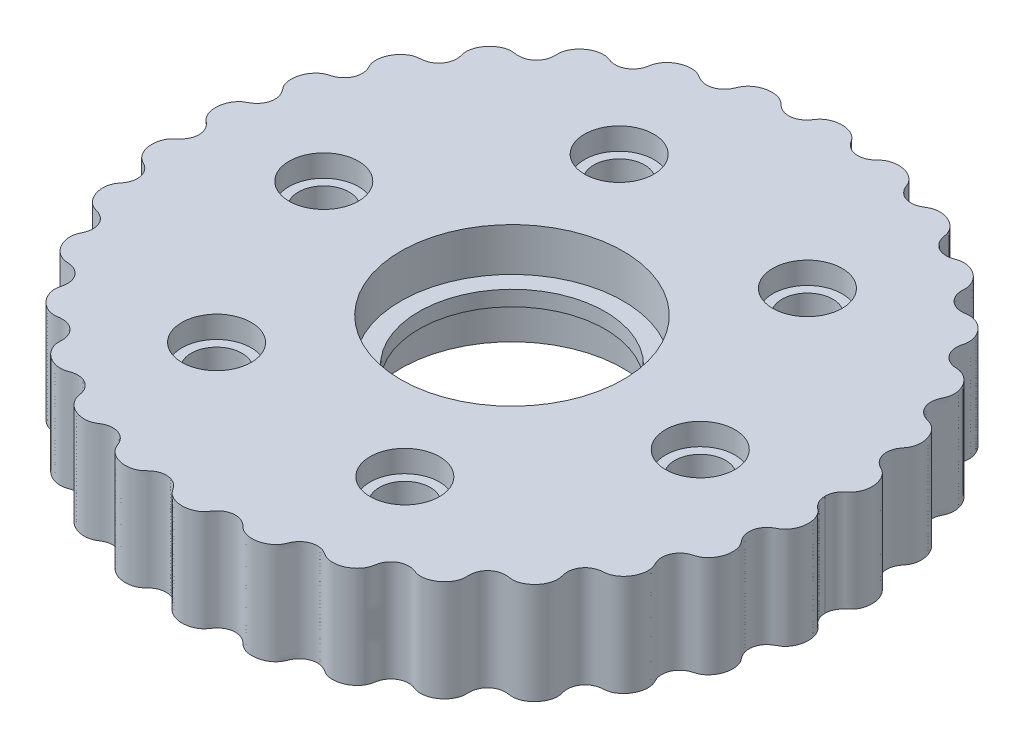
SolidWorks part; units mm, degrees
ref_plane "Front Plane" through (0, 0, 0) normal (0, 0, 1) x (1, 0, 0)
ref_plane "Top Plane" through (0, 0, 0) normal (0, 1, 0) x (1, 0, 0)
ref_plane "Right Plane" through (0, 0, 0) normal (1, 0, 0) x (0, 0, -1)
sketch "Sketch5" plane through (0, 0, 0) normal (0, 1, 0) x (1, 0, 0)
  line L0 (-37, 0) -> (37, 0) construction
  spline S0 degree 4 poles (33.6201, 15.9032) (33.6202, 15.6059) (33.7016, 15.1701) (33.9687, 14.6432) (34.4643, 14.1903) (34.8255, 13.9864) (35.1244, 13.8732) (35.3415, 13.8086) (35.5156, 13.7581) (35.7286, 13.6806) (35.9914, 13.5445) (36.2852, 13.3283) (36.665, 12.9337) (36.969, 12.4366) (37.1692, 11.88) (37.2514, 11.2873) (37.2381, 10.8555) (37.1706, 10.4918) (37.0784, 10.2135) (36.9889, 10.0153) (36.8865, 9.8401) (36.7761, 9.6875) (36.6303, 9.5028) (36.4666, 9.2723) (36.3182, 8.9951) (36.2055, 8.6691) (36.1476, 8.346) (36.1382, 8.0344) (36.1741, 7.7336) (36.2499, 7.4499) (36.3608, 7.1872) (36.4999, 6.9493) (36.6697, 6.7308) (36.8638, 6.5368) (37.0837, 6.3658) (37.2851, 6.2419) (37.4707, 6.1434) (37.6377, 6.0496) (37.7133, 6.0018) (37.8076, 5.9345) (37.8984, 5.863) (37.9811, 5.7906) (38.0693, 5.7029) (38.1661, 5.5944) (38.2783, 5.4519) (38.399, 5.2711) (38.5204, 5.048) (38.632, 4.7801) (38.7165, 4.5026) (38.7833, 4.1716) (38.8153, 3.7874) (38.7918, 3.3544) (38.7009, 2.943) (38.5724, 2.606) (38.4358, 2.3521) (38.3147, 2.1727) (38.1838, 2.0152) (38.0457, 1.8805) (37.8982, 1.7564) (37.7521, 1.6308) (37.5791, 1.4629) (37.4056, 1.2571) (37.2454, 1.0066) (37.0836, 0.6399) (36.9813, 0.1918) (36.9899, -0.2712) (37.1093, -0.7163) (37.2863, -1.079) (37.4568, -1.3245) (37.6384, -1.5249) (37.8168, -1.688) (37.9652, -1.8118) (38.1102, -1.9399) (38.2421, -2.0817) (38.365, -2.2432) (38.4766, -2.4235) (38.6007, -2.6735) (38.7542, -3.1094) (38.8303, -3.6329) (38.7943, -4.224) (38.6368, -4.7979) (38.4589, -5.1833) (38.2594, -5.4872) (38.0695, -5.707) (37.9109, -5.8569) (37.747, -5.9826) (37.5812, -6.0843) (37.4093, -6.175) (37.2395, -6.2696) (37.0351, -6.4013) (36.8234, -6.5711) (36.6166, -6.7879) (36.3864, -7.1195) (36.2027, -7.5374) (36.124, -7.9871) (36.1536, -8.4372) (36.2505, -8.8154) (36.363, -9.0822) (36.4942, -9.3093) (36.6301, -9.501) (36.7457, -9.6491) (36.8873, -9.8367) (37.0113, -10.0513) (37.1094, -10.2922) (37.1963, -10.6114) (37.2619, -11.0816) (37.2287, -11.6216) (37.0672, -12.2031) (36.7876, -12.7384) (36.5295, -13.0795) (36.2674, -13.3353) (36.0326, -13.51) (35.8436, -13.6225) (35.6546, -13.7096) (35.4689, -13.7728) (35.2331, -13.8388) (34.9539, -13.9315) (34.663, -14.073) (34.3764, -14.2756) (34.0851, -14.5596) (33.8252, -14.936) (33.6633, -15.3628) (33.6075, -15.809) (33.6302, -16.1955) (33.6888, -16.4767) (33.7726, -16.723) (33.867, -16.9362) (33.9492, -17.1036) (34.0456, -17.316) (34.1183, -17.551) (34.1611, -17.8055) (34.1766, -18.1335) (34.14, -18.603) (33.9938, -19.1195) (33.7153, -19.6496) (33.3326, -20.1109) (33.0116, -20.3886) (32.7046, -20.5829) (32.4408, -20.7045) (32.2343, -20.7752) (32.033, -20.8216) (31.8399, -20.8454) (31.6459, -20.8581) (31.4523, -20.8764) (31.2122, -20.9152) (30.9459, -20.9874) (30.6617, -21.1078) (30.3048, -21.3326) (29.9643, -21.6601) (29.7179, -22.0563) (29.577, -22.489) (29.5259, -22.8695) (29.5291, -23.1544) (29.563, -23.4104) (29.6127, -23.6364) (29.6581, -23.8158) (29.7052, -24.0426) (29.7238, -24.2861) (29.7102, -24.5417) (29.6547, -24.8628) (29.519, -25.3099) (29.267, -25.7821) (28.8818, -26.2416) (28.4067, -26.613) (28.0278, -26.8178) (27.6806, -26.9421) (27.3918, -27.003) (27.1705, -27.0259) (26.9596, -27.0248) (26.7616, -27.0031) (26.5647, -26.9745) (26.3665, -26.955) (26.1175, -26.9486) (25.761, -26.9788) (25.3089, -27.1043) (24.824, -27.3909) (24.4148, -27.8339) (24.1717, -28.3154) (24.0729, -28.7303) (24.0489, -29.0616) (24.0521, -29.3012) (24.0594, -29.4928) (24.0546, -29.7327) (24.0067, -30.0355) (23.8897, -30.3895) (23.6285, -30.877) (23.2487, -31.3196) (22.7798, -31.682) (22.2395, -31.9429) (21.8227, -32.063) (21.4542, -32.11) (21.1569, -32.1068) (20.9344, -32.0806) (20.7275, -32.0326) (20.5377, -31.9678) (20.3495, -31.899) (20.1577, -31.84) (19.9131, -31.7845) (19.5549, -31.7447) (19.0835, -31.7814) (18.5507, -31.9717) (18.1214, -32.2883) (17.8376, -32.6242) (17.6504, -32.9447) (17.5448, -33.2022) (17.4764, -33.4473) (17.4324, -33.6738) (17.4006, -33.8556) (17.3478, -34.0803) (17.2617, -34.3078) (17.1426, -34.5327) (16.9591, -34.7991) (16.6522, -35.1459) (16.2287, -35.47) (15.6877, -35.7293) (15.0983, -35.8712) (14.6623, -35.8998) (14.2898, -35.8662) (13.9982, -35.7981) (13.7853, -35.7234) (13.5928, -35.6303) (13.4203, -35.5252) (13.2488, -35.4186) (13.0713, -35.3221) (12.8406, -35.2189) (12.4944, -35.1096) (12.0211, -35.0548) (11.4595, -35.141) (10.9769, -35.3716) (10.6351, -35.6476) (10.3919, -35.9248) (10.2401, -36.1555) (10.1263, -36.3806) (10.0387, -36.5915) (9.9697, -36.7607) (9.8693, -36.966) (9.7364, -37.1668) (9.5727, -37.3587) (9.3378, -37.5772) (8.9665, -37.8479) (8.4908, -38.0712) (7.9192, -38.2085) (7.3291, -38.2262) (6.9124, -38.1699) (6.5666, -38.0695) (6.2983, -37.9513) (6.1011, -37.8386) (5.9227, -37.7081) (5.7648, -37.5629) (5.6114, -37.4135) (5.4491, -37.2733) (5.2327, -37.1149) (4.9037, -36.9312) (4.4389, -36.7814) (3.8653, -36.7592) (3.2834, -36.9106) (2.8288, -37.176) (2.5313, -37.4532) (2.3359, -37.6983) (2.2101, -37.8812) (2.1102, -38.0281) (1.9736, -38.2034) (1.7711, -38.4048) (1.4894, -38.6107) (1.026, -38.8446) (0.498, -38.9852) (-0.0532, -39.0229) (-0.6059, -38.9535) (-0.99, -38.8438) (-1.303, -38.7063) (-1.5774, -38.5452) (-1.7771, -38.395) (-1.9495, -38.23) (-2.0917, -38.0539) (-2.1944, -37.9049) (-2.3215, -37.7179) (-2.518, -37.4668) (-2.8184, -37.1828) (-3.2772, -36.9124) (-3.8631, -36.7591) (-4.4389, -36.7814) (-4.9037, -36.9312) (-5.2327, -37.1149) (-5.4491, -37.2733) (-5.6114, -37.4135) (-5.7648, -37.5629) (-5.9227, -37.7081) (-6.1011, -37.8386) (-6.2983, -37.9513) (-6.5666, -38.0695) (-6.9124, -38.1699) (-7.3291, -38.2262) (-7.9192, -38.2085) (-8.4908, -38.0712) (-8.9665, -37.8479) (-9.3378, -37.5772) (-9.5727, -37.3587) (-9.7364, -37.1668) (-9.8693, -36.966) (-9.9697, -36.7607) (-10.0387, -36.5915) (-10.1263, -36.3806) (-10.2713, -36.0937) (-10.5133, -35.755) (-10.9138, -35.4018) (-11.4595, -35.141) (-12.0211, -35.0548) (-12.4944, -35.1096) (-12.8406, -35.2189) (-13.0713, -35.3221) (-13.2488, -35.4186) (-13.4203, -35.5252) (-13.5928, -35.6303) (-13.7853, -35.7234) (-13.9982, -35.7981) (-14.2898, -35.8662) (-14.6623, -35.8998) (-15.0983, -35.8712) (-15.6877, -35.7293) (-16.2287, -35.47) (-16.6522, -35.1459) (-16.9591, -34.7991) (-17.1426, -34.5327) (-17.2617, -34.3078) (-17.3478, -34.0803) (-17.4006, -33.8556) (-17.4324, -33.6738) (-17.4764, -33.4473) (-17.5448, -33.2022) (-17.6504, -32.9447) (-17.8376, -32.6242) (-18.1214, -32.2883) (-18.5507, -31.9717) (-19.0835, -31.7814) (-19.5549, -31.7447) (-19.9131, -31.7845) (-20.1577, -31.84) (-20.3495, -31.899) (-20.5377, -31.9678) (-20.7275, -32.0326) (-20.9344, -32.0806) (-21.1569, -32.1068) (-21.4542, -32.11) (-21.8227, -32.063) (-22.2395, -31.9429) (-22.7798, -31.682) (-23.2487, -31.3196) (-23.6285, -30.877) (-23.8897, -30.3895) (-24.0067, -30.0355) (-24.0546, -29.7327) (-24.0594, -29.4928) (-24.0521, -29.3012) (-24.0489, -29.0616) (-24.0729, -28.7303) (-24.1717, -28.3154) (-24.4148, -27.8339) (-24.824, -27.3909) (-25.3089, -27.1043) (-25.761, -26.9788) (-26.1175, -26.9486) (-26.3665, -26.955) (-26.5647, -26.9745) (-26.7616, -27.0031) (-26.9596, -27.0248) (-27.1705, -27.0259) (-27.3918, -27.003) (-27.6806, -26.9421) (-28.0278, -26.8178) (-28.4067, -26.613) (-28.8818, -26.2416) (-29.267, -25.7821) (-29.519, -25.3099) (-29.6547, -24.8628) (-29.7102, -24.5417) (-29.7238, -24.2861) (-29.7052, -24.0426) (-29.6581, -23.8158) (-29.6127, -23.6364) (-29.563, -23.4104) (-29.5291, -23.1544) (-29.5259, -22.8695) (-29.577, -22.489) (-29.7179, -22.0563) (-29.9643, -21.6601) (-30.3048, -21.3326) (-30.6617, -21.1078) (-30.9459, -20.9874) (-31.2122, -20.9152) (-31.4523, -20.8764) (-31.6459, -20.8581) (-31.8399, -20.8454) (-32.033, -20.8216) (-32.2343, -20.7752) (-32.4408, -20.7045) (-32.7046, -20.5829) (-33.0116, -20.3886) (-33.3326, -20.1109) (-33.7153, -19.6496) (-33.9938, -19.1195) (-34.14, -18.603) (-34.1766, -18.1335) (-34.1611, -17.8055) (-34.1183, -17.551) (-34.0456, -17.316) (-33.9492, -17.1036) (-33.867, -16.9362) (-33.7726, -16.723) (-33.6888, -16.4767) (-33.6302, -16.1955) (-33.6075, -15.809) (-33.6633, -15.3628) (-33.8252, -14.936) (-34.0851, -14.5596) (-34.3764, -14.2756) (-34.663, -14.073) (-34.9539, -13.9315) (-35.2331, -13.8388) (-35.4689, -13.7728) (-35.6546, -13.7096) (-35.8436, -13.6225) (-36.0326, -13.51) (-36.2674, -13.3353) (-36.5295, -13.0795) (-36.7876, -12.7384) (-37.0672, -12.2031) (-37.2287, -11.6216) (-37.2619, -11.0816) (-37.1963, -10.6114) (-37.1094, -10.2922) (-37.0113, -10.0513) (-36.8873, -9.8367) (-36.7457, -9.6491) (-36.6301, -9.501) (-36.4942, -9.3093) (-36.363, -9.0822) (-36.2505, -8.8154) (-36.1536, -8.4372) (-36.124, -7.9871) (-36.2027, -7.5374) (-36.3864, -7.1195) (-36.6166, -6.7879) (-36.8234, -6.5711) (-37.0351, -6.4013) (-37.2395, -6.2696) (-37.4093, -6.175) (-37.5812, -6.0843) (-37.747, -5.9826) (-37.9109, -5.8569) (-38.0695, -5.707) (-38.2594, -5.4872) (-38.4589, -5.1833) (-38.6368, -4.7979) (-38.7943, -4.224) (-38.8303, -3.6329) (-38.7542, -3.1094) (-38.6007, -2.6735) (-38.4766, -2.4235) (-38.365, -2.2432) (-38.2421, -2.0817) (-38.1102, -1.9399) (-37.9652, -1.8118) (-37.8168, -1.688) (-37.6384, -1.5249) (-37.4568, -1.3245) (-37.2863, -1.079) (-37.1093, -0.7163) (-36.9899, -0.2712) (-36.9813, 0.1918) (-37.0836, 0.6399) (-37.2454, 1.0066) (-37.4056, 1.2571) (-37.5791, 1.4629) (-37.7521, 1.6308) (-37.8982, 1.7564) (-38.0457, 1.8805) (-38.1838, 2.0152) (-38.3147, 2.1727) (-38.4358, 2.3521) (-38.5724, 2.606) (-38.7009, 2.943) (-38.7918, 3.3544) (-38.8153, 3.7874) (-38.7833, 4.1716) (-38.7166, 4.5025) (-38.6319, 4.7801) (-38.5205, 5.0479) (-38.3815, 5.3031) (-38.2372, 5.5113) (-38.0948, 5.6776) (-37.9681, 5.8034) (-37.8575, 5.8983) (-37.7246, 5.9947) (-37.6376, 6.0497) (-37.4708, 6.1433) (-37.2851, 6.2419) (-37.0838, 6.3658) (-36.8638, 6.5368) (-36.6697, 6.7308) (-36.4999, 6.9493) (-36.3608, 7.1872) (-36.2499, 7.4499) (-36.1741, 7.7336) (-36.1382, 8.0344) (-36.1476, 8.346) (-36.2055, 8.6691) (-36.3182, 8.9951) (-36.4666, 9.2723) (-36.6303, 9.5028) (-36.7761, 9.6875) (-36.8865, 9.8401) (-36.9889, 10.0153) (-37.0784, 10.2135) (-37.1706, 10.4918) (-37.2381, 10.8555) (-37.2514, 11.2873) (-37.1815, 11.7914) (-37.0233, 12.2913) (-36.8053, 12.7086) (-36.5571, 13.0424) (-36.315, 13.2895) (-36.1009, 13.4649) (-35.8769, 13.6072) (-35.6471, 13.7153) (-35.4163, 13.7882) (-35.1948, 13.8503) (-34.9234, 13.9467) (-34.613, 14.1006) (-34.2264, 14.3849) (-33.8416, 14.866) (-33.6649, 15.3373) (-33.6202, 15.7145) (-33.6201, 15.9032) knots 0 0 0 0 0 0.006684 0.009785 0.012886 0.014922 0.015941 0.016959 0.017977 0.018995 0.021032 0.023585 0.026137 0.031243 0.034004 0.036765 0.039525 0.040906 0.042286 0.043344 0.044402 0.04546 0.046518 0.048633 0.050749 0.052495 0.05424 0.055985 0.057731 0.059277 0.060824 0.06237 0.063917 0.065463 0.06701 0.068556 0.06933 0.070103 0.070917 0.071324 0.071731 0.072545 0.073358 0.074172 0.074986 0.076614 0.078242 0.07987 0.081498 0.083125 0.085819 0.088512 0.091205 0.092551 0.093898 0.09498 0.096063 0.097146 0.098229 0.099311 0.100394 0.10256 0.104263 0.105967 0.109374 0.112808 0.114525 0.116242 0.118414 0.119501 0.120587 0.121673 0.12276 0.123846 0.124933 0.126227 0.127521 0.13011 0.135287 0.138001 0.140714 0.143428 0.144784 0.146141 0.147233 0.148325 0.149417 0.150509 0.151601 0.152694 0.154878 0.156593 0.158307 0.161737 0.165054 0.166713 0.168372 0.170483 0.171539 0.172595 0.173651 0.174706 0.176818 0.178147 0.179476 0.182134 0.187449 0.190183 0.192916 0.195649 0.197016 0.198383 0.199484 0.200585 0.201686 0.202787 0.204988 0.20719 0.208918 0.210645 0.214099 0.217389 0.219034 0.220679 0.222775 0.223822 0.22487 0.225918 0.226966 0.229061 0.23038 0.231699 0.234336 0.239611 0.242324 0.245036 0.247749 0.249105 0.250461 0.251554 0.252646 0.253739 0.254831 0.255924 0.257016 0.259201 0.261016 0.262831 0.266461 0.269723 0.271354 0.272985 0.275065 0.276105 0.277145 0.278185 0.279225 0.281305 0.282614 0.283922 0.286539 0.291773 0.294526 0.297278 0.300031 0.301407 0.302783 0.303901 0.30502 0.306138 0.307257 0.308375 0.309494 0.311731 0.315276 0.318821 0.321963 0.325104 0.327259 0.328336 0.329413 0.33049 0.331568 0.333722 0.336275 0.338828 0.343935 0.346707 0.349479 0.352252 0.353638 0.355024 0.35615 0.357277 0.358403 0.359529 0.360656 0.361782 0.364035 0.367607 0.371179 0.374303 0.375864 0.377426 0.3795 0.380536 0.381573 0.38261 0.383647 0.385721 0.387018 0.388315 0.390909 0.396097 0.398888 0.40168 0.404471 0.405867 0.407262 0.408397 0.409531 0.410666 0.4118 0.412935 0.41407 0.416339 0.419937 0.423536 0.426643 0.428196 0.42975 0.431803 0.432829 0.433856 0.434882 0.435909 0.437962 0.439249 0.440536 0.44311 0.448259 0.450946 0.453634 0.456322 0.457666 0.45901 0.460214 0.461418 0.462622 0.463826 0.46503 0.466234 0.468642 0.472266 0.47589 0.478933 0.481976 0.483972 0.48497 0.485968 0.486966 0.487964 0.48996 0.492365 0.49477 0.49958 0.502134 0.504689 0.507243 0.50852 0.509798 0.511831 0.512847 0.513864 0.51488 0.515897 0.51793 0.52102 0.52411 0.527734 0.531358 0.533766 0.53497 0.536174 0.537378 0.538582 0.539786 0.54099 0.542334 0.543678 0.546366 0.549054 0.551742 0.55689 0.559464 0.560751 0.562038 0.564091 0.565118 0.566144 0.567171 0.568197 0.57025 0.573357 0.576464 0.580063 0.583662 0.585931 0.587065 0.5882 0.589334 0.590469 0.591603 0.592738 0.594134 0.595529 0.598321 0.601112 0.603903 0.609091 0.611685 0.612982 0.614279 0.616353 0.61739 0.618427 0.619464 0.620501 0.622575 0.624136 0.625698 0.628821 0.632393 0.635966 0.638218 0.639345 0.640471 0.641597 0.642724 0.64385 0.644976 0.646363 0.647749 0.650521 0.653293 0.656065 0.661172 0.663725 0.666278 0.668433 0.66951 0.670587 0.671664 0.672742 0.674896 0.678038 0.681179 0.684725 0.68827 0.690507 0.691625 0.692743 0.693862 0.69498 0.696099 0.697217 0.698593 0.69997 0.702722 0.705475 0.708227 0.713461 0.716078 0.717386 0.718695 0.720775 0.721815 0.722855 0.723895 0.724935 0.727015 0.728646 0.730278 0.73354 0.737169 0.738984 0.740799 0.742984 0.744076 0.745169 0.746261 0.747354 0.748446 0.749539 0.750895 0.752251 0.754964 0.757677 0.760389 0.765664 0.768302 0.76962 0.770939 0.773035 0.774082 0.77513 0.776178 0.777226 0.779321 0.780966 0.782611 0.785901 0.789355 0.791083 0.79281 0.795012 0.797214 0.798315 0.799416 0.800517 0.801618 0.802984 0.804351 0.807084 0.809818 0.812551 0.817867 0.820524 0.821853 0.823182 0.825294 0.82635 0.827405 0.828461 0.829517 0.831629 0.833287 0.834946 0.838263 0.841693 0.843408 0.845123 0.847307 0.848399 0.849491 0.850583 0.851675 0.852767 0.853859 0.855216 0.856573 0.859286 0.861999 0.864713 0.86989 0.872479 0.873773 0.875068 0.876154 0.87724 0.878327 0.879413 0.8805 0.881586 0.883759 0.885475 0.887192 0.890626 0.894033 0.895737 0.89744 0.899606 0.900689 0.901772 0.902854 0.903937 0.90502 0.906103 0.907449 0.908796 0.911489 0.914182 0.916875 0.918503 0.92013 0.921758 0.923386 0.925014 0.926642 0.927456 0.92827 0.929084 0.929897 0.930671 0.931444 0.93299 0.934537 0.936083 0.93763 0.939176 0.940723 0.942269 0.944015 0.94576 0.947506 0.949251 0.951367 0.953483 0.954541 0.955598 0.956656 0.957714 0.959095 0.960475 0.963236 0.965996 0.968757 0.971861 0.974966 0.976518 0.97807 0.979622 0.981175 0.982468 0.983761 0.985054 0.986347 0.988934 0.99152 0.99576 1 1 1 1 1 construction
  spline S1 degree 4 poles (37, 0) (37, -0.0093) (37.001, -0.1714) (37.0271, -0.4097) (37.1093, -0.7163) (37.2863, -1.079) (37.4568, -1.3245) (37.6384, -1.5249) (37.8168, -1.688) (37.9652, -1.8118) (38.1102, -1.9399) (38.2421, -2.0817) (38.365, -2.2432) (38.4766, -2.4235) (38.6007, -2.6735) (38.7542, -3.1094) (38.8303, -3.6329) (38.7943, -4.224) (38.6368, -4.7979) (38.4589, -5.1833) (38.2594, -5.4872) (38.0695, -5.707) (37.9109, -5.8569) (37.747, -5.9826) (37.5812, -6.0843) (37.4093, -6.175) (37.2395, -6.2696) (37.0351, -6.4013) (36.8234, -6.5711) (36.6166, -6.7879) (36.3864, -7.1195) (36.2027, -7.5374) (36.124, -7.9871) (36.1536, -8.4372) (36.2505, -8.8154) (36.363, -9.0822) (36.4942, -9.3093) (36.6301, -9.501) (36.7457, -9.6491) (36.8873, -9.8367) (37.0113, -10.0513) (37.1094, -10.2922) (37.1963, -10.6114) (37.2619, -11.0816) (37.2287, -11.6216) (37.0672, -12.2031) (36.7876, -12.7384) (36.5295, -13.0795) (36.2674, -13.3353) (36.0326, -13.51) (35.8436, -13.6225) (35.6546, -13.7096) (35.4689, -13.7728) (35.2331, -13.8388) (34.9539, -13.9315) (34.663, -14.073) (34.3764, -14.2756) (34.0851, -14.5596) (33.8252, -14.936) (33.6633, -15.3628) (33.6075, -15.809) (33.6302, -16.1955) (33.6888, -16.4767) (33.7726, -16.723) (33.867, -16.9362) (33.9492, -17.1036) (34.0456, -17.316) (34.1183, -17.551) (34.1611, -17.8055) (34.1766, -18.1335) (34.14, -18.603) (33.9938, -19.1195) (33.7153, -19.6496) (33.3326, -20.1109) (33.0116, -20.3886) (32.7046, -20.5829) (32.4408, -20.7045) (32.2343, -20.7752) (32.033, -20.8216) (31.8399, -20.8454) (31.6459, -20.8581) (31.4523, -20.8764) (31.2122, -20.9152) (30.9459, -20.9874) (30.6617, -21.1078) (30.3048, -21.3326) (29.9643, -21.6601) (29.7179, -22.0563) (29.577, -22.489) (29.5259, -22.8695) (29.5291, -23.1544) (29.563, -23.4104) (29.6127, -23.6364) (29.6581, -23.8158) (29.7052, -24.0426) (29.7238, -24.2861) (29.7102, -24.5417) (29.6547, -24.8628) (29.519, -25.3099) (29.267, -25.7821) (28.8818, -26.2416) (28.4067, -26.613) (28.0278, -26.8178) (27.6806, -26.9421) (27.3918, -27.003) (27.1705, -27.0259) (26.9596, -27.0248) (26.7616, -27.0031) (26.5647, -26.9745) (26.3665, -26.955) (26.1175, -26.9486) (25.761, -26.9788) (25.3089, -27.1043) (24.824, -27.3909) (24.4148, -27.8339) (24.1717, -28.3154) (24.0729, -28.7303) (24.0489, -29.0616) (24.0521, -29.3012) (24.0594, -29.4928) (24.0546, -29.7327) (24.0067, -30.0355) (23.8897, -30.3895) (23.6285, -30.877) (23.2487, -31.3196) (22.7798, -31.682) (22.2395, -31.9429) (21.8227, -32.063) (21.4542, -32.11) (21.1569, -32.1068) (20.9344, -32.0806) (20.7275, -32.0326) (20.5377, -31.9678) (20.3495, -31.899) (20.1577, -31.84) (19.9131, -31.7845) (19.5549, -31.7447) (19.0835, -31.7814) (18.5507, -31.9717) (18.1214, -32.2883) (17.8376, -32.6242) (17.6504, -32.9447) (17.5448, -33.2022) (17.4764, -33.4473) (17.4324, -33.6738) (17.4006, -33.8556) (17.3478, -34.0803) (17.2617, -34.3078) (17.1426, -34.5327) (16.9591, -34.7991) (16.6522, -35.1459) (16.2287, -35.47) (15.6877, -35.7293) (15.0983, -35.8712) (14.6623, -35.8998) (14.2898, -35.8662) (13.9982, -35.7981) (13.7853, -35.7234) (13.5928, -35.6303) (13.4203, -35.5252) (13.2488, -35.4186) (13.0713, -35.3221) (12.8406, -35.2189) (12.4944, -35.1096) (12.0211, -35.0548) (11.4595, -35.141) (10.9769, -35.3716) (10.6351, -35.6476) (10.3919, -35.9248) (10.2401, -36.1555) (10.1263, -36.3806) (10.0387, -36.5915) (9.9697, -36.7607) (9.8693, -36.966) (9.7364, -37.1668) (9.5727, -37.3587) (9.3378, -37.5772) (8.9665, -37.8479) (8.4908, -38.0712) (7.9192, -38.2085) (7.3291, -38.2262) (6.9124, -38.1699) (6.5666, -38.0695) (6.2983, -37.9513) (6.1011, -37.8386) (5.9227, -37.7081) (5.7648, -37.5629) (5.6114, -37.4135) (5.4491, -37.2733) (5.2327, -37.1149) (4.9037, -36.9312) (4.4389, -36.7814) (3.8653, -36.7592) (3.2834, -36.9106) (2.8288, -37.176) (2.5313, -37.4532) (2.3359, -37.6983) (2.2101, -37.8812) (2.1102, -38.0281) (1.9736, -38.2034) (1.7711, -38.4048) (1.4894, -38.6107) (1.026, -38.8446) (0.498, -38.9852) (-0.0532, -39.0229) (-0.6059, -38.9535) (-0.99, -38.8438) (-1.303, -38.7063) (-1.5774, -38.5452) (-1.7771, -38.395) (-1.9495, -38.23) (-2.0917, -38.0539) (-2.1944, -37.9049) (-2.3215, -37.7179) (-2.518, -37.4668) (-2.8184, -37.1828) (-3.2772, -36.9124) (-3.8631, -36.7591) (-4.4389, -36.7814) (-4.9037, -36.9312) (-5.2327, -37.1149) (-5.4491, -37.2733) (-5.6114, -37.4135) (-5.7648, -37.5629) (-5.9227, -37.7081) (-6.1011, -37.8386) (-6.2983, -37.9513) (-6.5666, -38.0695) (-6.9124, -38.1699) (-7.3291, -38.2262) (-7.9192, -38.2085) (-8.4908, -38.0712) (-8.9665, -37.8479) (-9.3378, -37.5772) (-9.5727, -37.3587) (-9.7364, -37.1668) (-9.8693, -36.966) (-9.9697, -36.7607) (-10.0387, -36.5915) (-10.1263, -36.3806) (-10.2713, -36.0937) (-10.5133, -35.755) (-10.9138, -35.4018) (-11.4595, -35.141) (-12.0211, -35.0548) (-12.4944, -35.1096) (-12.8406, -35.2189) (-13.0713, -35.3221) (-13.2488, -35.4186) (-13.4203, -35.5252) (-13.5928, -35.6303) (-13.7853, -35.7234) (-13.9982, -35.7981) (-14.2898, -35.8662) (-14.6623, -35.8998) (-15.0983, -35.8712) (-15.6877, -35.7293) (-16.2287, -35.47) (-16.6522, -35.1459) (-16.9591, -34.7991) (-17.1426, -34.5327) (-17.2617, -34.3078) (-17.3478, -34.0803) (-17.4006, -33.8556) (-17.4324, -33.6738) (-17.4764, -33.4473) (-17.5448, -33.2022) (-17.6504, -32.9447) (-17.8376, -32.6242) (-18.1214, -32.2883) (-18.5507, -31.9717) (-19.0835, -31.7814) (-19.5549, -31.7447) (-19.9131, -31.7845) (-20.1577, -31.84) (-20.3495, -31.899) (-20.5377, -31.9678) (-20.7275, -32.0326) (-20.9344, -32.0806) (-21.1569, -32.1068) (-21.4542, -32.11) (-21.8227, -32.063) (-22.2395, -31.9429) (-22.7798, -31.682) (-23.2487, -31.3196) (-23.6285, -30.877) (-23.8897, -30.3895) (-24.0067, -30.0355) (-24.0546, -29.7327) (-24.0594, -29.4928) (-24.0521, -29.3012) (-24.0489, -29.0616) (-24.0729, -28.7303) (-24.1717, -28.3154) (-24.4148, -27.8339) (-24.824, -27.3909) (-25.3089, -27.1043) (-25.761, -26.9788) (-26.1175, -26.9486) (-26.3665, -26.955) (-26.5647, -26.9745) (-26.7616, -27.0031) (-26.9596, -27.0248) (-27.1705, -27.0259) (-27.3918, -27.003) (-27.6806, -26.9421) (-28.0278, -26.8178) (-28.4067, -26.613) (-28.8818, -26.2416) (-29.267, -25.7821) (-29.519, -25.3099) (-29.6547, -24.8628) (-29.7102, -24.5417) (-29.7238, -24.2861) (-29.7052, -24.0426) (-29.6581, -23.8158) (-29.6127, -23.6364) (-29.563, -23.4104) (-29.5291, -23.1544) (-29.5259, -22.8695) (-29.577, -22.489) (-29.7179, -22.0563) (-29.9643, -21.6601) (-30.3048, -21.3326) (-30.6617, -21.1078) (-30.9459, -20.9874) (-31.2122, -20.9152) (-31.4523, -20.8764) (-31.6459, -20.8581) (-31.8399, -20.8454) (-32.033, -20.8216) (-32.2343, -20.7752) (-32.4408, -20.7045) (-32.7046, -20.5829) (-33.0116, -20.3886) (-33.3326, -20.1109) (-33.7153, -19.6496) (-33.9938, -19.1195) (-34.14, -18.603) (-34.1766, -18.1335) (-34.1611, -17.8055) (-34.1183, -17.551) (-34.0456, -17.316) (-33.9492, -17.1036) (-33.867, -16.9362) (-33.7726, -16.723) (-33.6888, -16.4767) (-33.6302, -16.1955) (-33.6075, -15.809) (-33.6633, -15.3628) (-33.8252, -14.936) (-34.0851, -14.5596) (-34.3764, -14.2756) (-34.663, -14.073) (-34.9539, -13.9315) (-35.2331, -13.8388) (-35.4689, -13.7728) (-35.6546, -13.7096) (-35.8436, -13.6225) (-36.0326, -13.51) (-36.2674, -13.3353) (-36.5295, -13.0795) (-36.7876, -12.7384) (-37.0672, -12.2031) (-37.2287, -11.6216) (-37.2619, -11.0816) (-37.1963, -10.6114) (-37.1094, -10.2922) (-37.0113, -10.0513) (-36.8873, -9.8367) (-36.7457, -9.6491) (-36.6301, -9.501) (-36.4942, -9.3093) (-36.363, -9.0822) (-36.2505, -8.8154) (-36.1536, -8.4372) (-36.124, -7.9871) (-36.2027, -7.5374) (-36.3864, -7.1195) (-36.6166, -6.7879) (-36.8234, -6.5711) (-37.0351, -6.4013) (-37.2395, -6.2696) (-37.4093, -6.175) (-37.5812, -6.0843) (-37.747, -5.9826) (-37.9109, -5.8569) (-38.0695, -5.707) (-38.2594, -5.4872) (-38.4589, -5.1833) (-38.6368, -4.7979) (-38.7943, -4.224) (-38.8303, -3.6329) (-38.7542, -3.1094) (-38.6007, -2.6735) (-38.4766, -2.4235) (-38.365, -2.2432) (-38.2421, -2.0817) (-38.1102, -1.9399) (-37.9652, -1.8118) (-37.8168, -1.688) (-37.6384, -1.5249) (-37.4568, -1.3245) (-37.2863, -1.079) (-37.1093, -0.7163) (-37.0271, -0.4097) (-37.001, -0.1714) (-37, -0.0093) (-37, 0) knots 0.109164 0.109164 0.109164 0.109164 0.109164 0.109374 0.112808 0.114525 0.116242 0.118414 0.119501 0.120587 0.121673 0.12276 0.123846 0.124933 0.126227 0.127521 0.13011 0.135287 0.138001 0.140714 0.143428 0.144784 0.146141 0.147233 0.148325 0.149417 0.150509 0.151601 0.152694 0.154878 0.156593 0.158307 0.161737 0.165054 0.166713 0.168372 0.170483 0.171539 0.172595 0.173651 0.174706 0.176818 0.178147 0.179476 0.182134 0.187449 0.190183 0.192916 0.195649 0.197016 0.198383 0.199484 0.200585 0.201686 0.202787 0.204988 0.20719 0.208918 0.210645 0.214099 0.217389 0.219034 0.220679 0.222775 0.223822 0.22487 0.225918 0.226966 0.229061 0.23038 0.231699 0.234336 0.239611 0.242324 0.245036 0.247749 0.249105 0.250461 0.251554 0.252646 0.253739 0.254831 0.255924 0.257016 0.259201 0.261016 0.262831 0.266461 0.269723 0.271354 0.272985 0.275065 0.276105 0.277145 0.278185 0.279225 0.281305 0.282614 0.283922 0.286539 0.291773 0.294526 0.297278 0.300031 0.301407 0.302783 0.303901 0.30502 0.306138 0.307257 0.308375 0.309494 0.311731 0.315276 0.318821 0.321963 0.325104 0.327259 0.328336 0.329413 0.33049 0.331568 0.333722 0.336275 0.338828 0.343935 0.346707 0.349479 0.352252 0.353638 0.355024 0.35615 0.357277 0.358403 0.359529 0.360656 0.361782 0.364035 0.367607 0.371179 0.374303 0.375864 0.377426 0.3795 0.380536 0.381573 0.38261 0.383647 0.385721 0.387018 0.388315 0.390909 0.396097 0.398888 0.40168 0.404471 0.405867 0.407262 0.408397 0.409531 0.410666 0.4118 0.412935 0.41407 0.416339 0.419937 0.423536 0.426643 0.428196 0.42975 0.431803 0.432829 0.433856 0.434882 0.435909 0.437962 0.439249 0.440536 0.44311 0.448259 0.450946 0.453634 0.456322 0.457666 0.45901 0.460214 0.461418 0.462622 0.463826 0.46503 0.466234 0.468642 0.472266 0.47589 0.478933 0.481976 0.483972 0.48497 0.485968 0.486966 0.487964 0.48996 0.492365 0.49477 0.49958 0.502134 0.504689 0.507243 0.50852 0.509798 0.511831 0.512847 0.513864 0.51488 0.515897 0.51793 0.52102 0.52411 0.527734 0.531358 0.533766 0.53497 0.536174 0.537378 0.538582 0.539786 0.54099 0.542334 0.543678 0.546366 0.549054 0.551742 0.55689 0.559464 0.560751 0.562038 0.564091 0.565118 0.566144 0.567171 0.568197 0.57025 0.573357 0.576464 0.580063 0.583662 0.585931 0.587065 0.5882 0.589334 0.590469 0.591603 0.592738 0.594134 0.595529 0.598321 0.601112 0.603903 0.609091 0.611685 0.612982 0.614279 0.616353 0.61739 0.618427 0.619464 0.620501 0.622575 0.624136 0.625698 0.628821 0.632393 0.635966 0.638218 0.639345 0.640471 0.641597 0.642724 0.64385 0.644976 0.646363 0.647749 0.650521 0.653293 0.656065 0.661172 0.663725 0.666278 0.668433 0.66951 0.670587 0.671664 0.672742 0.674896 0.678038 0.681179 0.684725 0.68827 0.690507 0.691625 0.692743 0.693862 0.69498 0.696099 0.697217 0.698593 0.69997 0.702722 0.705475 0.708227 0.713461 0.716078 0.717386 0.718695 0.720775 0.721815 0.722855 0.723895 0.724935 0.727015 0.728646 0.730278 0.73354 0.737169 0.738984 0.740799 0.742984 0.744076 0.745169 0.746261 0.747354 0.748446 0.749539 0.750895 0.752251 0.754964 0.757677 0.760389 0.765664 0.768302 0.76962 0.770939 0.773035 0.774082 0.77513 0.776178 0.777226 0.779321 0.780966 0.782611 0.785901 0.789355 0.791083 0.79281 0.795012 0.797214 0.798315 0.799416 0.800517 0.801618 0.802984 0.804351 0.807084 0.809818 0.812551 0.817867 0.820524 0.821853 0.823182 0.825294 0.82635 0.827405 0.828461 0.829517 0.831629 0.833287 0.834946 0.838263 0.841693 0.843408 0.845123 0.847307 0.848399 0.849491 0.850583 0.851675 0.852767 0.853859 0.855216 0.856573 0.859286 0.861999 0.864713 0.86989 0.872479 0.873773 0.875068 0.876154 0.87724 0.878327 0.879413 0.8805 0.881586 0.883759 0.885475 0.887192 0.890626 0.890836 0.890836 0.890836 0.890836 0.890836
  spline S2 degree 4 poles (37, 0) (37, 0.0093) (37.001, 0.1714) (37.0271, 0.4097) (37.1093, 0.7163) (37.2863, 1.079) (37.4568, 1.3245) (37.6384, 1.5249) (37.8168, 1.688) (37.9652, 1.8118) (38.1102, 1.9399) (38.2421, 2.0817) (38.365, 2.2432) (38.4766, 2.4235) (38.6007, 2.6735) (38.7542, 3.1094) (38.8303, 3.6329) (38.7943, 4.224) (38.6368, 4.7979) (38.4589, 5.1833) (38.2594, 5.4872) (38.0695, 5.707) (37.9109, 5.8569) (37.747, 5.9826) (37.5812, 6.0843) (37.4093, 6.175) (37.2395, 6.2696) (37.0351, 6.4013) (36.8234, 6.5711) (36.6166, 6.7879) (36.3864, 7.1195) (36.2027, 7.5374) (36.124, 7.9871) (36.1536, 8.4372) (36.2505, 8.8154) (36.363, 9.0822) (36.4942, 9.3093) (36.6301, 9.501) (36.7457, 9.6491) (36.8873, 9.8367) (37.0113, 10.0513) (37.1094, 10.2922) (37.1963, 10.6114) (37.2619, 11.0816) (37.2287, 11.6216) (37.0672, 12.2031) (36.7876, 12.7384) (36.5295, 13.0795) (36.2674, 13.3353) (36.0326, 13.51) (35.8436, 13.6225) (35.6546, 13.7096) (35.4689, 13.7728) (35.2331, 13.8388) (34.9539, 13.9315) (34.663, 14.073) (34.3764, 14.2756) (34.0851, 14.5596) (33.8252, 14.936) (33.6633, 15.3628) (33.6075, 15.809) (33.6302, 16.1955) (33.6888, 16.4767) (33.7726, 16.723) (33.867, 16.9362) (33.9492, 17.1036) (34.0456, 17.316) (34.1183, 17.551) (34.1611, 17.8055) (34.1766, 18.1335) (34.14, 18.603) (33.9938, 19.1195) (33.7153, 19.6496) (33.3326, 20.1109) (33.0116, 20.3886) (32.7046, 20.5829) (32.4408, 20.7045) (32.2343, 20.7752) (32.033, 20.8216) (31.8399, 20.8454) (31.6459, 20.8581) (31.4523, 20.8764) (31.2122, 20.9152) (30.9459, 20.9874) (30.6617, 21.1078) (30.3048, 21.3326) (29.9643, 21.6601) (29.7179, 22.0563) (29.577, 22.489) (29.5259, 22.8695) (29.5291, 23.1544) (29.563, 23.4104) (29.6127, 23.6364) (29.6581, 23.8158) (29.7052, 24.0426) (29.7238, 24.2861) (29.7102, 24.5417) (29.6547, 24.8628) (29.519, 25.3099) (29.267, 25.7821) (28.8818, 26.2416) (28.4067, 26.613) (28.0278, 26.8178) (27.6806, 26.9421) (27.3918, 27.003) (27.1705, 27.0259) (26.9596, 27.0248) (26.7616, 27.0031) (26.5647, 26.9745) (26.3665, 26.955) (26.1175, 26.9486) (25.761, 26.9788) (25.3089, 27.1043) (24.824, 27.3909) (24.4148, 27.8339) (24.1717, 28.3154) (24.0729, 28.7303) (24.0489, 29.0616) (24.0521, 29.3012) (24.0594, 29.4928) (24.0546, 29.7327) (24.0067, 30.0355) (23.8897, 30.3895) (23.6285, 30.877) (23.2487, 31.3196) (22.7798, 31.682) (22.2395, 31.9429) (21.8227, 32.063) (21.4542, 32.11) (21.1569, 32.1068) (20.9344, 32.0806) (20.7275, 32.0326) (20.5377, 31.9678) (20.3495, 31.899) (20.1577, 31.84) (19.9131, 31.7845) (19.5549, 31.7447) (19.0835, 31.7814) (18.5507, 31.9717) (18.1214, 32.2883) (17.8376, 32.6242) (17.6504, 32.9447) (17.5448, 33.2022) (17.4764, 33.4473) (17.4324, 33.6738) (17.4006, 33.8556) (17.3478, 34.0803) (17.2617, 34.3078) (17.1426, 34.5327) (16.9591, 34.7991) (16.6522, 35.1459) (16.2287, 35.47) (15.6877, 35.7293) (15.0983, 35.8712) (14.6623, 35.8998) (14.2898, 35.8662) (13.9982, 35.7981) (13.7853, 35.7234) (13.5928, 35.6303) (13.4203, 35.5252) (13.2488, 35.4186) (13.0713, 35.3221) (12.8406, 35.2189) (12.4944, 35.1096) (12.0211, 35.0548) (11.4595, 35.141) (10.9769, 35.3716) (10.6351, 35.6476) (10.3919, 35.9248) (10.2401, 36.1555) (10.1263, 36.3806) (10.0387, 36.5915) (9.9697, 36.7607) (9.8693, 36.966) (9.7364, 37.1668) (9.5727, 37.3587) (9.3378, 37.5772) (8.9665, 37.8479) (8.4908, 38.0712) (7.9192, 38.2085) (7.3291, 38.2262) (6.9124, 38.1699) (6.5666, 38.0695) (6.2983, 37.9513) (6.1011, 37.8386) (5.9227, 37.7081) (5.7648, 37.5629) (5.6114, 37.4135) (5.4491, 37.2733) (5.2327, 37.1149) (4.9037, 36.9312) (4.4389, 36.7814) (3.8653, 36.7592) (3.2834, 36.9106) (2.8288, 37.176) (2.5313, 37.4532) (2.3359, 37.6983) (2.2101, 37.8812) (2.1102, 38.0281) (1.9736, 38.2034) (1.7711, 38.4048) (1.4894, 38.6107) (1.026, 38.8446) (0.498, 38.9852) (-0.0532, 39.0229) (-0.6059, 38.9535) (-0.99, 38.8438) (-1.303, 38.7063) (-1.5774, 38.5452) (-1.7771, 38.395) (-1.9495, 38.23) (-2.0917, 38.0539) (-2.1944, 37.9049) (-2.3215, 37.7179) (-2.518, 37.4668) (-2.8184, 37.1828) (-3.2772, 36.9124) (-3.8631, 36.7591) (-4.4389, 36.7814) (-4.9037, 36.9312) (-5.2327, 37.1149) (-5.4491, 37.2733) (-5.6114, 37.4135) (-5.7648, 37.5629) (-5.9227, 37.7081) (-6.1011, 37.8386) (-6.2983, 37.9513) (-6.5666, 38.0695) (-6.9124, 38.1699) (-7.3291, 38.2262) (-7.9192, 38.2085) (-8.4908, 38.0712) (-8.9665, 37.8479) (-9.3378, 37.5772) (-9.5727, 37.3587) (-9.7364, 37.1668) (-9.8693, 36.966) (-9.9697, 36.7607) (-10.0387, 36.5915) (-10.1263, 36.3806) (-10.2713, 36.0937) (-10.5133, 35.755) (-10.9138, 35.4018) (-11.4595, 35.141) (-12.0211, 35.0548) (-12.4944, 35.1096) (-12.8406, 35.2189) (-13.0713, 35.3221) (-13.2488, 35.4186) (-13.4203, 35.5252) (-13.5928, 35.6303) (-13.7853, 35.7234) (-13.9982, 35.7981) (-14.2898, 35.8662) (-14.6623, 35.8998) (-15.0983, 35.8712) (-15.6877, 35.7293) (-16.2287, 35.47) (-16.6522, 35.1459) (-16.9591, 34.7991) (-17.1426, 34.5327) (-17.2617, 34.3078) (-17.3478, 34.0803) (-17.4006, 33.8556) (-17.4324, 33.6738) (-17.4764, 33.4473) (-17.5448, 33.2022) (-17.6504, 32.9447) (-17.8376, 32.6242) (-18.1214, 32.2883) (-18.5507, 31.9717) (-19.0835, 31.7814) (-19.5549, 31.7447) (-19.9131, 31.7845) (-20.1577, 31.84) (-20.3495, 31.899) (-20.5377, 31.9678) (-20.7275, 32.0326) (-20.9344, 32.0806) (-21.1569, 32.1068) (-21.4542, 32.11) (-21.8227, 32.063) (-22.2395, 31.9429) (-22.7798, 31.682) (-23.2487, 31.3196) (-23.6285, 30.877) (-23.8897, 30.3895) (-24.0067, 30.0355) (-24.0546, 29.7327) (-24.0594, 29.4928) (-24.0521, 29.3012) (-24.0489, 29.0616) (-24.0729, 28.7303) (-24.1717, 28.3154) (-24.4148, 27.8339) (-24.824, 27.3909) (-25.3089, 27.1043) (-25.761, 26.9788) (-26.1175, 26.9486) (-26.3665, 26.955) (-26.5647, 26.9745) (-26.7616, 27.0031) (-26.9596, 27.0248) (-27.1705, 27.0259) (-27.3918, 27.003) (-27.6806, 26.9421) (-28.0278, 26.8178) (-28.4067, 26.613) (-28.8818, 26.2416) (-29.267, 25.7821) (-29.519, 25.3099) (-29.6547, 24.8628) (-29.7102, 24.5417) (-29.7238, 24.2861) (-29.7052, 24.0426) (-29.6581, 23.8158) (-29.6127, 23.6364) (-29.563, 23.4104) (-29.5291, 23.1544) (-29.5259, 22.8695) (-29.577, 22.489) (-29.7179, 22.0563) (-29.9643, 21.6601) (-30.3048, 21.3326) (-30.6617, 21.1078) (-30.9459, 20.9874) (-31.2122, 20.9152) (-31.4523, 20.8764) (-31.6459, 20.8581) (-31.8399, 20.8454) (-32.033, 20.8216) (-32.2343, 20.7752) (-32.4408, 20.7045) (-32.7046, 20.5829) (-33.0116, 20.3886) (-33.3326, 20.1109) (-33.7153, 19.6496) (-33.9938, 19.1195) (-34.14, 18.603) (-34.1766, 18.1335) (-34.1611, 17.8055) (-34.1183, 17.551) (-34.0456, 17.316) (-33.9492, 17.1036) (-33.867, 16.9362) (-33.7726, 16.723) (-33.6888, 16.4767) (-33.6302, 16.1955) (-33.6075, 15.809) (-33.6633, 15.3628) (-33.8252, 14.936) (-34.0851, 14.5596) (-34.3764, 14.2756) (-34.663, 14.073) (-34.9539, 13.9315) (-35.2331, 13.8388) (-35.4689, 13.7728) (-35.6546, 13.7096) (-35.8436, 13.6225) (-36.0326, 13.51) (-36.2674, 13.3353) (-36.5295, 13.0795) (-36.7876, 12.7384) (-37.0672, 12.2031) (-37.2287, 11.6216) (-37.2619, 11.0816) (-37.1963, 10.6114) (-37.1094, 10.2922) (-37.0113, 10.0513) (-36.8873, 9.8367) (-36.7457, 9.6491) (-36.6301, 9.501) (-36.4942, 9.3093) (-36.363, 9.0822) (-36.2505, 8.8154) (-36.1536, 8.4372) (-36.124, 7.9871) (-36.2027, 7.5374) (-36.3864, 7.1195) (-36.6166, 6.7879) (-36.8234, 6.5711) (-37.0351, 6.4013) (-37.2395, 6.2696) (-37.4093, 6.175) (-37.5812, 6.0843) (-37.747, 5.9826) (-37.9109, 5.8569) (-38.0695, 5.707) (-38.2594, 5.4872) (-38.4589, 5.1833) (-38.6368, 4.7979) (-38.7943, 4.224) (-38.8303, 3.6329) (-38.7542, 3.1094) (-38.6007, 2.6735) (-38.4766, 2.4235) (-38.365, 2.2432) (-38.2421, 2.0817) (-38.1102, 1.9399) (-37.9652, 1.8118) (-37.8168, 1.688) (-37.6384, 1.5249) (-37.4568, 1.3245) (-37.2863, 1.079) (-37.1093, 0.7163) (-37.0271, 0.4097) (-37.001, 0.1714) (-37, 0.0093) (-37, 0) knots 0.109164 0.109164 0.109164 0.109164 0.109164 0.109374 0.112808 0.114525 0.116242 0.118414 0.119501 0.120587 0.121673 0.12276 0.123846 0.124933 0.126227 0.127521 0.13011 0.135287 0.138001 0.140714 0.143428 0.144784 0.146141 0.147233 0.148325 0.149417 0.150509 0.151601 0.152694 0.154878 0.156593 0.158307 0.161737 0.165054 0.166713 0.168372 0.170483 0.171539 0.172595 0.173651 0.174706 0.176818 0.178147 0.179476 0.182134 0.187449 0.190183 0.192916 0.195649 0.197016 0.198383 0.199484 0.200585 0.201686 0.202787 0.204988 0.20719 0.208918 0.210645 0.214099 0.217389 0.219034 0.220679 0.222775 0.223822 0.22487 0.225918 0.226966 0.229061 0.23038 0.231699 0.234336 0.239611 0.242324 0.245036 0.247749 0.249105 0.250461 0.251554 0.252646 0.253739 0.254831 0.255924 0.257016 0.259201 0.261016 0.262831 0.266461 0.269723 0.271354 0.272985 0.275065 0.276105 0.277145 0.278185 0.279225 0.281305 0.282614 0.283922 0.286539 0.291773 0.294526 0.297278 0.300031 0.301407 0.302783 0.303901 0.30502 0.306138 0.307257 0.308375 0.309494 0.311731 0.315276 0.318821 0.321963 0.325104 0.327259 0.328336 0.329413 0.33049 0.331568 0.333722 0.336275 0.338828 0.343935 0.346707 0.349479 0.352252 0.353638 0.355024 0.35615 0.357277 0.358403 0.359529 0.360656 0.361782 0.364035 0.367607 0.371179 0.374303 0.375864 0.377426 0.3795 0.380536 0.381573 0.38261 0.383647 0.385721 0.387018 0.388315 0.390909 0.396097 0.398888 0.40168 0.404471 0.405867 0.407262 0.408397 0.409531 0.410666 0.4118 0.412935 0.41407 0.416339 0.419937 0.423536 0.426643 0.428196 0.42975 0.431803 0.432829 0.433856 0.434882 0.435909 0.437962 0.439249 0.440536 0.44311 0.448259 0.450946 0.453634 0.456322 0.457666 0.45901 0.460214 0.461418 0.462622 0.463826 0.46503 0.466234 0.468642 0.472266 0.47589 0.478933 0.481976 0.483972 0.48497 0.485968 0.486966 0.487964 0.48996 0.492365 0.49477 0.49958 0.502134 0.504689 0.507243 0.50852 0.509798 0.511831 0.512847 0.513864 0.51488 0.515897 0.51793 0.52102 0.52411 0.527734 0.531358 0.533766 0.53497 0.536174 0.537378 0.538582 0.539786 0.54099 0.542334 0.543678 0.546366 0.549054 0.551742 0.55689 0.559464 0.560751 0.562038 0.564091 0.565118 0.566144 0.567171 0.568197 0.57025 0.573357 0.576464 0.580063 0.583662 0.585931 0.587065 0.5882 0.589334 0.590469 0.591603 0.592738 0.594134 0.595529 0.598321 0.601112 0.603903 0.609091 0.611685 0.612982 0.614279 0.616353 0.61739 0.618427 0.619464 0.620501 0.622575 0.624136 0.625698 0.628821 0.632393 0.635966 0.638218 0.639345 0.640471 0.641597 0.642724 0.64385 0.644976 0.646363 0.647749 0.650521 0.653293 0.656065 0.661172 0.663725 0.666278 0.668433 0.66951 0.670587 0.671664 0.672742 0.674896 0.678038 0.681179 0.684725 0.68827 0.690507 0.691625 0.692743 0.693862 0.69498 0.696099 0.697217 0.698593 0.69997 0.702722 0.705475 0.708227 0.713461 0.716078 0.717386 0.718695 0.720775 0.721815 0.722855 0.723895 0.724935 0.727015 0.728646 0.730278 0.73354 0.737169 0.738984 0.740799 0.742984 0.744076 0.745169 0.746261 0.747354 0.748446 0.749539 0.750895 0.752251 0.754964 0.757677 0.760389 0.765664 0.768302 0.76962 0.770939 0.773035 0.774082 0.77513 0.776178 0.777226 0.779321 0.780966 0.782611 0.785901 0.789355 0.791083 0.79281 0.795012 0.797214 0.798315 0.799416 0.800517 0.801618 0.802984 0.804351 0.807084 0.809818 0.812551 0.817867 0.820524 0.821853 0.823182 0.825294 0.82635 0.827405 0.828461 0.829517 0.831629 0.833287 0.834946 0.838263 0.841693 0.843408 0.845123 0.847307 0.848399 0.849491 0.850583 0.851675 0.852767 0.853859 0.855216 0.856573 0.859286 0.861999 0.864713 0.86989 0.872479 0.873773 0.875068 0.876154 0.87724 0.878327 0.879413 0.8805 0.881586 0.883759 0.885475 0.887192 0.890626 0.890836 0.890836 0.890836 0.890836 0.890836
extrude "Boss-Extrude2" add sketch "Sketch5" along normal blind 12
sketch "Sketch6" plane through (0, 12, 0) normal (0, 1, 0) x (1, 0, 0)
  line L0 (0, 0) -> (-38.7864, 4.0766) construction
  circle A0 centre (0, 0) radius 15 construction
  circle A1 centre (-24.863, 2.6132) radius 4.1
  circle A3 centre (-10.1684, 22.8386) radius 4.1
  circle A4 centre (14.6946, 20.2254) radius 4.1
  circle A5 centre (24.863, -2.6132) radius 4.1
  circle A6 centre (10.1684, -22.8386) radius 4.1
  circle A7 centre (-14.6946, -20.2254) radius 4.1
  spline S0 degree 4 poles (37, 0) (37, 0.0093) (37.001, 0.1714) (37.0271, 0.4097) (37.1093, 0.7163) (37.2863, 1.079) (37.4568, 1.3245) (37.6384, 1.5249) (37.8168, 1.688) (37.9652, 1.8118) (38.1102, 1.9399) (38.2421, 2.0817) (38.365, 2.2432) (38.4766, 2.4235) (38.6007, 2.6735) (38.7542, 3.1094) (38.8303, 3.6329) (38.7943, 4.224) (38.6368, 4.7979) (38.4589, 5.1833) (38.2594, 5.4872) (38.0695, 5.707) (37.9109, 5.8569) (37.747, 5.9826) (37.5812, 6.0843) (37.4093, 6.175) (37.2395, 6.2696) (37.0351, 6.4013) (36.8234, 6.5711) (36.6166, 6.7879) (36.3864, 7.1195) (36.2027, 7.5374) (36.124, 7.9871) (36.1536, 8.4372) (36.2505, 8.8154) (36.363, 9.0822) (36.4942, 9.3093) (36.6301, 9.501) (36.7457, 9.6491) (36.8873, 9.8367) (37.0113, 10.0513) (37.1094, 10.2922) (37.1963, 10.6114) (37.2619, 11.0816) (37.2287, 11.6216) (37.0672, 12.2031) (36.7876, 12.7384) (36.5295, 13.0795) (36.2674, 13.3353) (36.0326, 13.51) (35.8436, 13.6225) (35.6546, 13.7096) (35.4689, 13.7728) (35.2331, 13.8388) (34.9539, 13.9315) (34.663, 14.073) (34.3764, 14.2756) (34.0851, 14.5596) (33.8252, 14.936) (33.6633, 15.3628) (33.6075, 15.809) (33.6302, 16.1955) (33.6888, 16.4767) (33.7726, 16.723) (33.867, 16.9362) (33.9492, 17.1036) (34.0456, 17.316) (34.1183, 17.551) (34.1611, 17.8055) (34.1766, 18.1335) (34.14, 18.603) (33.9938, 19.1195) (33.7153, 19.6496) (33.3326, 20.1109) (33.0116, 20.3886) (32.7046, 20.5829) (32.4408, 20.7045) (32.2343, 20.7752) (32.033, 20.8216) (31.8399, 20.8454) (31.6459, 20.8581) (31.4523, 20.8764) (31.2122, 20.9152) (30.9459, 20.9874) (30.6617, 21.1078) (30.3048, 21.3326) (29.9643, 21.6601) (29.7179, 22.0563) (29.577, 22.489) (29.5259, 22.8695) (29.5291, 23.1544) (29.563, 23.4104) (29.6127, 23.6364) (29.6581, 23.8158) (29.7052, 24.0426) (29.7238, 24.2861) (29.7102, 24.5417) (29.6547, 24.8628) (29.519, 25.3099) (29.267, 25.7821) (28.8818, 26.2416) (28.4067, 26.613) (28.0278, 26.8178) (27.6806, 26.9421) (27.3918, 27.003) (27.1705, 27.0259) (26.9596, 27.0248) (26.7616, 27.0031) (26.5647, 26.9745) (26.3665, 26.955) (26.1175, 26.9486) (25.761, 26.9788) (25.3089, 27.1043) (24.824, 27.3909) (24.4148, 27.8339) (24.1717, 28.3154) (24.0729, 28.7303) (24.0489, 29.0616) (24.0521, 29.3012) (24.0594, 29.4928) (24.0546, 29.7327) (24.0067, 30.0355) (23.8897, 30.3895) (23.6285, 30.877) (23.2487, 31.3196) (22.7798, 31.682) (22.2395, 31.9429) (21.8227, 32.063) (21.4542, 32.11) (21.1569, 32.1068) (20.9344, 32.0806) (20.7275, 32.0326) (20.5377, 31.9678) (20.3495, 31.899) (20.1577, 31.84) (19.9131, 31.7845) (19.5549, 31.7447) (19.0835, 31.7814) (18.5507, 31.9717) (18.1214, 32.2883) (17.8376, 32.6242) (17.6504, 32.9447) (17.5448, 33.2022) (17.4764, 33.4473) (17.4324, 33.6738) (17.4006, 33.8556) (17.3478, 34.0803) (17.2617, 34.3078) (17.1426, 34.5327) (16.9591, 34.7991) (16.6522, 35.1459) (16.2287, 35.47) (15.6877, 35.7293) (15.0983, 35.8712) (14.6623, 35.8998) (14.2898, 35.8662) (13.9982, 35.7981) (13.7853, 35.7234) (13.5928, 35.6303) (13.4203, 35.5252) (13.2488, 35.4186) (13.0713, 35.3221) (12.8406, 35.2189) (12.4944, 35.1096) (12.0211, 35.0548) (11.4595, 35.141) (10.9769, 35.3716) (10.6351, 35.6476) (10.3919, 35.9248) (10.2401, 36.1555) (10.1263, 36.3806) (10.0387, 36.5915) (9.9697, 36.7607) (9.8693, 36.966) (9.7364, 37.1668) (9.5727, 37.3587) (9.3378, 37.5772) (8.9665, 37.8479) (8.4908, 38.0712) (7.9192, 38.2085) (7.3291, 38.2262) (6.9124, 38.1699) (6.5666, 38.0695) (6.2983, 37.9513) (6.1011, 37.8386) (5.9227, 37.7081) (5.7648, 37.5629) (5.6114, 37.4135) (5.4491, 37.2733) (5.2327, 37.1149) (4.9037, 36.9312) (4.4389, 36.7814) (3.8653, 36.7592) (3.2834, 36.9106) (2.8288, 37.176) (2.5313, 37.4532) (2.3359, 37.6983) (2.2101, 37.8812) (2.1102, 38.0281) (1.9736, 38.2034) (1.7711, 38.4048) (1.4894, 38.6107) (1.026, 38.8446) (0.498, 38.9852) (-0.0532, 39.0229) (-0.6059, 38.9535) (-0.99, 38.8438) (-1.303, 38.7063) (-1.5774, 38.5452) (-1.7771, 38.395) (-1.9495, 38.23) (-2.0917, 38.0539) (-2.1944, 37.9049) (-2.3215, 37.7179) (-2.518, 37.4668) (-2.8184, 37.1828) (-3.2772, 36.9124) (-3.8631, 36.7591) (-4.4389, 36.7814) (-4.9037, 36.9312) (-5.2327, 37.1149) (-5.4491, 37.2733) (-5.6114, 37.4135) (-5.7648, 37.5629) (-5.9227, 37.7081) (-6.1011, 37.8386) (-6.2983, 37.9513) (-6.5666, 38.0695) (-6.9124, 38.1699) (-7.3291, 38.2262) (-7.9192, 38.2085) (-8.4908, 38.0712) (-8.9665, 37.8479) (-9.3378, 37.5772) (-9.5727, 37.3587) (-9.7364, 37.1668) (-9.8693, 36.966) (-9.9697, 36.7607) (-10.0387, 36.5915) (-10.1263, 36.3806) (-10.2713, 36.0937) (-10.5133, 35.755) (-10.9138, 35.4018) (-11.4595, 35.141) (-12.0211, 35.0548) (-12.4944, 35.1096) (-12.8406, 35.2189) (-13.0713, 35.3221) (-13.2488, 35.4186) (-13.4203, 35.5252) (-13.5928, 35.6303) (-13.7853, 35.7234) (-13.9982, 35.7981) (-14.2898, 35.8662) (-14.6623, 35.8998) (-15.0983, 35.8712) (-15.6877, 35.7293) (-16.2287, 35.47) (-16.6522, 35.1459) (-16.9591, 34.7991) (-17.1426, 34.5327) (-17.2617, 34.3078) (-17.3478, 34.0803) (-17.4006, 33.8556) (-17.4324, 33.6738) (-17.4764, 33.4473) (-17.5448, 33.2022) (-17.6504, 32.9447) (-17.8376, 32.6242) (-18.1214, 32.2883) (-18.5507, 31.9717) (-19.0835, 31.7814) (-19.5549, 31.7447) (-19.9131, 31.7845) (-20.1577, 31.84) (-20.3495, 31.899) (-20.5377, 31.9678) (-20.7275, 32.0326) (-20.9344, 32.0806) (-21.1569, 32.1068) (-21.4542, 32.11) (-21.8227, 32.063) (-22.2395, 31.9429) (-22.7798, 31.682) (-23.2487, 31.3196) (-23.6285, 30.877) (-23.8897, 30.3895) (-24.0067, 30.0355) (-24.0546, 29.7327) (-24.0594, 29.4928) (-24.0521, 29.3012) (-24.0489, 29.0616) (-24.0729, 28.7303) (-24.1717, 28.3154) (-24.4148, 27.8339) (-24.824, 27.3909) (-25.3089, 27.1043) (-25.761, 26.9788) (-26.1175, 26.9486) (-26.3665, 26.955) (-26.5647, 26.9745) (-26.7616, 27.0031) (-26.9596, 27.0248) (-27.1705, 27.0259) (-27.3918, 27.003) (-27.6806, 26.9421) (-28.0278, 26.8178) (-28.4067, 26.613) (-28.8818, 26.2416) (-29.267, 25.7821) (-29.519, 25.3099) (-29.6547, 24.8628) (-29.7102, 24.5417) (-29.7238, 24.2861) (-29.7052, 24.0426) (-29.6581, 23.8158) (-29.6127, 23.6364) (-29.563, 23.4104) (-29.5291, 23.1544) (-29.5259, 22.8695) (-29.577, 22.489) (-29.7179, 22.0563) (-29.9643, 21.6601) (-30.3048, 21.3326) (-30.6617, 21.1078) (-30.9459, 20.9874) (-31.2122, 20.9152) (-31.4523, 20.8764) (-31.6459, 20.8581) (-31.8399, 20.8454) (-32.033, 20.8216) (-32.2343, 20.7752) (-32.4408, 20.7045) (-32.7046, 20.5829) (-33.0116, 20.3886) (-33.3326, 20.1109) (-33.7153, 19.6496) (-33.9938, 19.1195) (-34.14, 18.603) (-34.1766, 18.1335) (-34.1611, 17.8055) (-34.1183, 17.551) (-34.0456, 17.316) (-33.9492, 17.1036) (-33.867, 16.9362) (-33.7726, 16.723) (-33.6888, 16.4767) (-33.6302, 16.1955) (-33.6075, 15.809) (-33.6633, 15.3628) (-33.8252, 14.936) (-34.0851, 14.5596) (-34.3764, 14.2756) (-34.663, 14.073) (-34.9539, 13.9315) (-35.2331, 13.8388) (-35.4689, 13.7728) (-35.6546, 13.7096) (-35.8436, 13.6225) (-36.0326, 13.51) (-36.2674, 13.3353) (-36.5295, 13.0795) (-36.7876, 12.7384) (-37.0672, 12.2031) (-37.2287, 11.6216) (-37.2619, 11.0816) (-37.1963, 10.6114) (-37.1094, 10.2922) (-37.0113, 10.0513) (-36.8873, 9.8367) (-36.7457, 9.6491) (-36.6301, 9.501) (-36.4942, 9.3093) (-36.363, 9.0822) (-36.2505, 8.8154) (-36.1536, 8.4372) (-36.124, 7.9871) (-36.2027, 7.5374) (-36.3864, 7.1195) (-36.6166, 6.7879) (-36.8234, 6.5711) (-37.0351, 6.4013) (-37.2395, 6.2696) (-37.4093, 6.175) (-37.5812, 6.0843) (-37.747, 5.9826) (-37.9109, 5.8569) (-38.0695, 5.707) (-38.2594, 5.4872) (-38.4589, 5.1833) (-38.6368, 4.7979) (-38.7943, 4.224) (-38.8303, 3.6329) (-38.7542, 3.1094) (-38.6007, 2.6735) (-38.4766, 2.4235) (-38.365, 2.2432) (-38.2421, 2.0817) (-38.1102, 1.9399) (-37.9652, 1.8118) (-37.8168, 1.688) (-37.6384, 1.5249) (-37.4568, 1.3245) (-37.2863, 1.079) (-37.1093, 0.7163) (-37.0271, 0.4097) (-37.001, 0.1714) (-37, 0.0093) (-37, 0) knots 0.109164 0.109164 0.109164 0.109164 0.109164 0.109374 0.112808 0.114525 0.116242 0.118414 0.119501 0.120587 0.121673 0.12276 0.123846 0.124933 0.126227 0.127521 0.13011 0.135287 0.138001 0.140714 0.143428 0.144784 0.146141 0.147233 0.148325 0.149417 0.150509 0.151601 0.152694 0.154878 0.156593 0.158307 0.161737 0.165054 0.166713 0.168372 0.170483 0.171539 0.172595 0.173651 0.174706 0.176818 0.178147 0.179476 0.182134 0.187449 0.190183 0.192916 0.195649 0.197016 0.198383 0.199484 0.200585 0.201686 0.202787 0.204988 0.20719 0.208918 0.210645 0.214099 0.217389 0.219034 0.220679 0.222775 0.223822 0.22487 0.225918 0.226966 0.229061 0.23038 0.231699 0.234336 0.239611 0.242324 0.245036 0.247749 0.249105 0.250461 0.251554 0.252646 0.253739 0.254831 0.255924 0.257016 0.259201 0.261016 0.262831 0.266461 0.269723 0.271354 0.272985 0.275065 0.276105 0.277145 0.278185 0.279225 0.281305 0.282614 0.283922 0.286539 0.291773 0.294526 0.297278 0.300031 0.301407 0.302783 0.303901 0.30502 0.306138 0.307257 0.308375 0.309494 0.311731 0.315276 0.318821 0.321963 0.325104 0.327259 0.328336 0.329413 0.33049 0.331568 0.333722 0.336275 0.338828 0.343935 0.346707 0.349479 0.352252 0.353638 0.355024 0.35615 0.357277 0.358403 0.359529 0.360656 0.361782 0.364035 0.367607 0.371179 0.374303 0.375864 0.377426 0.3795 0.380536 0.381573 0.38261 0.383647 0.385721 0.387018 0.388315 0.390909 0.396097 0.398888 0.40168 0.404471 0.405867 0.407262 0.408397 0.409531 0.410666 0.4118 0.412935 0.41407 0.416339 0.419937 0.423536 0.426643 0.428196 0.42975 0.431803 0.432829 0.433856 0.434882 0.435909 0.437962 0.439249 0.440536 0.44311 0.448259 0.450946 0.453634 0.456322 0.457666 0.45901 0.460214 0.461418 0.462622 0.463826 0.46503 0.466234 0.468642 0.472266 0.47589 0.478933 0.481976 0.483972 0.48497 0.485968 0.486966 0.487964 0.48996 0.492365 0.49477 0.49958 0.502134 0.504689 0.507243 0.50852 0.509798 0.511831 0.512847 0.513864 0.51488 0.515897 0.51793 0.52102 0.52411 0.527734 0.531358 0.533766 0.53497 0.536174 0.537378 0.538582 0.539786 0.54099 0.542334 0.543678 0.546366 0.549054 0.551742 0.55689 0.559464 0.560751 0.562038 0.564091 0.565118 0.566144 0.567171 0.568197 0.57025 0.573357 0.576464 0.580063 0.583662 0.585931 0.587065 0.5882 0.589334 0.590469 0.591603 0.592738 0.594134 0.595529 0.598321 0.601112 0.603903 0.609091 0.611685 0.612982 0.614279 0.616353 0.61739 0.618427 0.619464 0.620501 0.622575 0.624136 0.625698 0.628821 0.632393 0.635966 0.638218 0.639345 0.640471 0.641597 0.642724 0.64385 0.644976 0.646363 0.647749 0.650521 0.653293 0.656065 0.661172 0.663725 0.666278 0.668433 0.66951 0.670587 0.671664 0.672742 0.674896 0.678038 0.681179 0.684725 0.68827 0.690507 0.691625 0.692743 0.693862 0.69498 0.696099 0.697217 0.698593 0.69997 0.702722 0.705475 0.708227 0.713461 0.716078 0.717386 0.718695 0.720775 0.721815 0.722855 0.723895 0.724935 0.727015 0.728646 0.730278 0.73354 0.737169 0.738984 0.740799 0.742984 0.744076 0.745169 0.746261 0.747354 0.748446 0.749539 0.750895 0.752251 0.754964 0.757677 0.760389 0.765664 0.768302 0.76962 0.770939 0.773035 0.774082 0.77513 0.776178 0.777226 0.779321 0.780966 0.782611 0.785901 0.789355 0.791083 0.79281 0.795012 0.797214 0.798315 0.799416 0.800517 0.801618 0.802984 0.804351 0.807084 0.809818 0.812551 0.817867 0.820524 0.821853 0.823182 0.825294 0.82635 0.827405 0.828461 0.829517 0.831629 0.833287 0.834946 0.838263 0.841693 0.843408 0.845123 0.847307 0.848399 0.849491 0.850583 0.851675 0.852767 0.853859 0.855216 0.856573 0.859286 0.861999 0.864713 0.86989 0.872479 0.873773 0.875068 0.876154 0.87724 0.878327 0.879413 0.8805 0.881586 0.883759 0.885475 0.887192 0.890626 0.890836 0.890836 0.890836 0.890836 0.890836 construction
  point P21 (0, 0)
  dimension "D1" = 8.2
  dimension "D2" = 30
  dimension "D3" = 25
  dimension "D4" = 6
extrude "Cut-Extrude1" cut sketch "Sketch6" against normal through all
sketch "Sketch7" plane through (0, 12, 0) normal (0, 1, 0) x (1, 0, 0)
  circle A0 centre (0, 0) radius 13.15
  dimension "D1" = 26.3
extrude "Cut-Extrude2" cut sketch "Sketch7" against normal through all
sketch "Sketch8" plane through (0, 0, 0) normal (0, -1, 0) x (1, 0, 0)
  circle A0 centre (0, 0) radius 31 construction
sketch "Sketch9" plane through (0, 0, 0) normal (0, -1, 0) x (1, 0, 0)
  circle A0 centre (-14.6946, 20.2254) radius 4.1
  circle A1 centre (-14.6946, 20.2254) radius 3
  point P4 (0, 0)
  dimension "D1" = 6
extrude "Boss-Extrude3" add sketch "Sketch9" against normal offset from surface (9.4 mm away) 2.6 up to face at (0, 12, 13.15)
pattern_circular "CirPattern1" count 6 over 360 about axis through (0, 0, 0) along (0, 1, 0) of "Boss-Extrude3"
ref_plane "Plane1" through (0, 6, 0) normal (0, 1, 0) x (1, 0, 0)
sketch "Sketch10" plane through (0, 6, 0) normal (0, 1, 0) x (1, 0, 0)
  circle A0 centre (0, 0) radius 15
  circle A1 centre (0, 0) radius 11
  dimension "D1" = 22
extrude "Boss-Extrude4" add sketch "Sketch10" along normal mid plane 1.8
